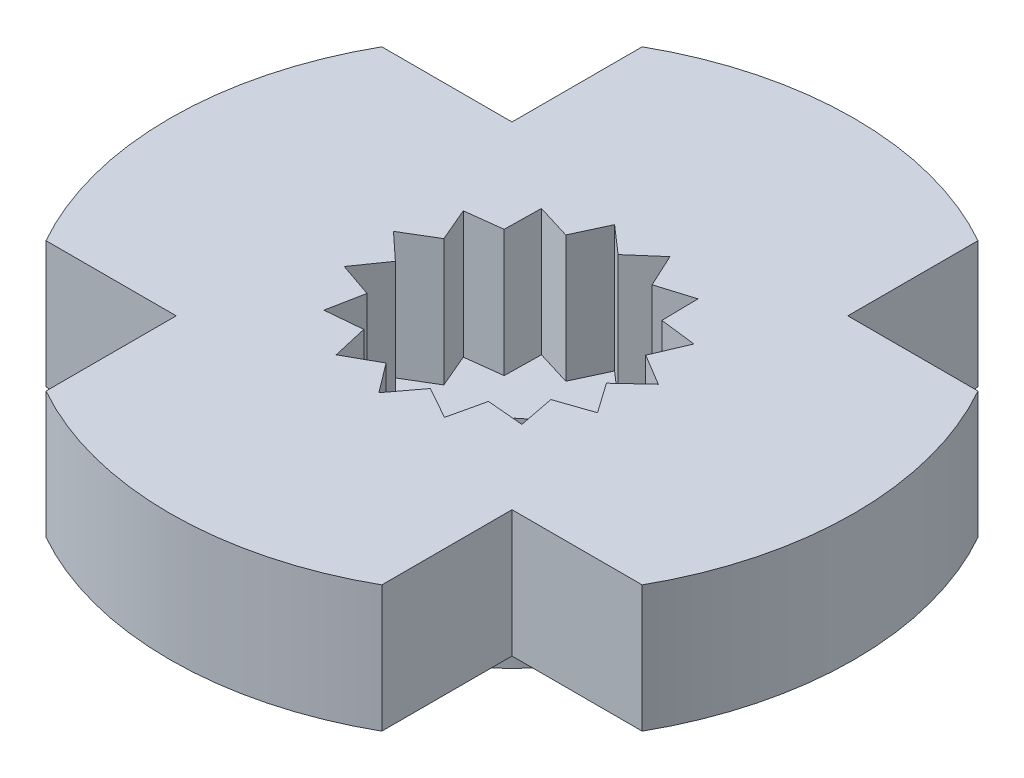
SolidWorks part; units mm, degrees
ref_plane "正面" through (0, 0, 0) normal (0, 0, 1) x (1, 0, 0)
ref_plane "平面" through (0, 0, 0) normal (0, 1, 0) x (1, 0, 0)
ref_plane "右側面" through (0, 0, 0) normal (1, 0, 0) x (0, 0, -1)
sketch "ｽｹｯﾁ1" plane through (0, 0, 0) normal (0, 1, 0) x (1, 0, 0)
  line L0 (0, 0) -> (0, 2.4324) construction
  line L1 (0, 0) -> (0.5057, 2.3792) construction
  line L2 (0, 0) -> (0.9893, 2.2221) construction
  line L3 (0, 0) -> (1.4297, 1.9678) construction
  line L4 (0, 0) -> (1.8076, 1.6276) construction
  line L5 (0, 0) -> (2.1065, 1.2162) construction
  line L6 (0, 0) -> (2.3133, 0.7516) construction
  line L7 (0, 0) -> (2.419, 0.2543) construction
  line L8 (0, 0) -> (2.419, -0.2543) construction
  line L9 (0, 0) -> (2.3133, -0.7516) construction
  line L10 (0, 0) -> (2.1065, -1.2162) construction
  line L11 (0, 0) -> (1.8076, -1.6276) construction
  line L12 (0, 0) -> (1.4297, -1.9678) construction
  line L13 (0, 0) -> (0.9893, -2.2221) construction
  line L14 (0, 0) -> (0.5057, -2.3792) construction
  line L15 (0, 0) -> (0, -2.4324) construction
  line L16 (0, 0) -> (-0.5057, -2.3792) construction
  line L17 (0, 0) -> (-0.9893, -2.2221) construction
  line L18 (0, 0) -> (-1.4297, -1.9678) construction
  line L19 (0, 0) -> (-1.8076, -1.6276) construction
  line L20 (0, 0) -> (-2.1065, -1.2162) construction
  line L21 (0, 0) -> (-2.3133, -0.7516) construction
  line L22 (0, 0) -> (-2.419, -0.2543) construction
  line L23 (0, 0) -> (-2.419, 0.2543) construction
  line L24 (0, 0) -> (-2.3133, 0.7516) construction
  line L25 (0, 0) -> (-2.1065, 1.2162) construction
  line L26 (0, 0) -> (-1.8076, 1.6276) construction
  line L27 (0, 0) -> (-1.4297, 1.9678) construction
  line L28 (0, 0) -> (-0.9893, 2.2221) construction
  line L29 (0, 0) -> (-0.5057, 2.3792) construction
  line L30 (0, 1.675) -> (0.437, 2.056)
  line L31 (0.6813, 1.5302) -> (1.2355, 1.7005)
  line L32 (0.6813, 1.5302) -> (0.437, 2.056)
  line L33 (1.2448, 1.1208) -> (1.8203, 1.051)
  line L34 (1.2448, 1.1208) -> (1.2355, 1.7005)
  line L35 (1.593, 0.5176) -> (2.0904, 0.2197)
  line L36 (1.593, 0.5176) -> (1.8203, 1.051)
  line L37 (1.6658, -0.1751) -> (1.9991, -0.6495)
  line L38 (1.6658, -0.1751) -> (2.0904, 0.2197)
  line L39 (1.4506, -0.8375) -> (1.562, -1.4065)
  line L40 (1.4506, -0.8375) -> (1.9991, -0.6495)
  line L41 (0.9845, -1.3551) -> (0.8549, -1.9202)
  line L42 (0.9845, -1.3551) -> (1.562, -1.4065)
  line L43 (0.3483, -1.6384) -> (0, -2.1019)
  line L44 (0.3483, -1.6384) -> (0.8549, -1.9202)
  line L45 (-0.3483, -1.6384) -> (-0.8549, -1.9202)
  line L46 (-0.3483, -1.6384) -> (0, -2.1019)
  line L47 (-0.9845, -1.3551) -> (-1.562, -1.4065)
  line L48 (-0.9845, -1.3551) -> (-0.8549, -1.9202)
  line L49 (-1.4506, -0.8375) -> (-1.9991, -0.6495)
  line L50 (-1.4506, -0.8375) -> (-1.562, -1.4065)
  line L51 (-1.6658, -0.1751) -> (-2.0904, 0.2197)
  line L52 (-1.6658, -0.1751) -> (-1.9991, -0.6495)
  line L53 (-1.593, 0.5176) -> (-1.8203, 1.051)
  line L54 (-1.593, 0.5176) -> (-2.0904, 0.2197)
  line L55 (-1.2448, 1.1208) -> (-1.2355, 1.7005)
  line L56 (-1.2448, 1.1208) -> (-1.8203, 1.051)
  line L57 (-0.6813, 1.5302) -> (-0.437, 2.056)
  line L58 (-0.6813, 1.5302) -> (-1.2355, 1.7005)
  line L59 (0, 1.675) -> (-0.437, 2.056)
  line L60 (2.65, 4.7051) -> (2.65, 2.65)
  line L61 (-2.65, 4.7051) -> (-2.65, 2.65)
  line L62 (0, 0) -> (-10.0301, 0) construction
  line L63 (-4.7051, 2.65) -> (-2.65, 2.65)
  line L64 (-4.7051, -2.65) -> (-2.65, -2.65)
  line L65 (-2.65, -2.65) -> (-2.65, -4.7051)
  line L66 (2.65, -2.65) -> (2.65, -4.7051)
  line L67 (2.65, 2.65) -> (4.7051, 2.65)
  line L68 (2.65, -2.65) -> (4.7051, -2.65)
  circle A0 centre (0, 0) radius 1.95 construction
  circle A1 centre (0, 0) radius 1.675 construction
  arc A2 (-4.7051, 2.65) -> (-4.7051, -2.65) centre (0, 0) ccw
  arc A3 (2.65, 4.7051) -> (-2.65, 4.7051) centre (0, 0) ccw
  arc A4 (4.7051, -2.65) -> (4.7051, 2.65) centre (0, 0) ccw
  arc A5 (-2.65, -4.7051) -> (2.65, -4.7051) centre (0, 0) ccw
  point P36 (0, 0)
  point P82 (0, 0)
  point P96 (0, 0)
  dimension "D1" = 3.9
  dimension "D2" = 3.35
  dimension "D6" = 5.4
  dimension "D4" = 15
  dimension "D5" = 2.65
  dimension "D7" = 2.65
  dimension "D8" = 2.65
  dimension "D9" = 2.65
  dimension "D3" = 30
extrude "ﾎﾞｽ - 押し出し1" add sketch "ｽｹｯﾁ1" along normal blind 2
sketch "ｽｹｯﾁ2" plane through (0, 0, 0) normal (0, -1, 0) x (1, 0, 0)
  circle A0 centre (0, 0) radius 2.575
  circle A1 centre (0, 0) radius 0.85
  dimension "D1" = 5.15
  dimension "D2" = 1.7
extrude "ﾎﾞｽ - 押し出し2" add sketch "ｽｹｯﾁ2" along normal blind 1
sketch "ｽｹｯﾁ3" plane through (0, -1, 0) normal (0, -1, 0) x (1, 0, 0)
  circle A0 centre (0, 0) radius 1.55
  dimension "D1" = 3.1
extrude "ｶｯﾄ - 押し出し1" [suppressed] cut sketch "ｽｹｯﾁ3" against normal blind 0.3
